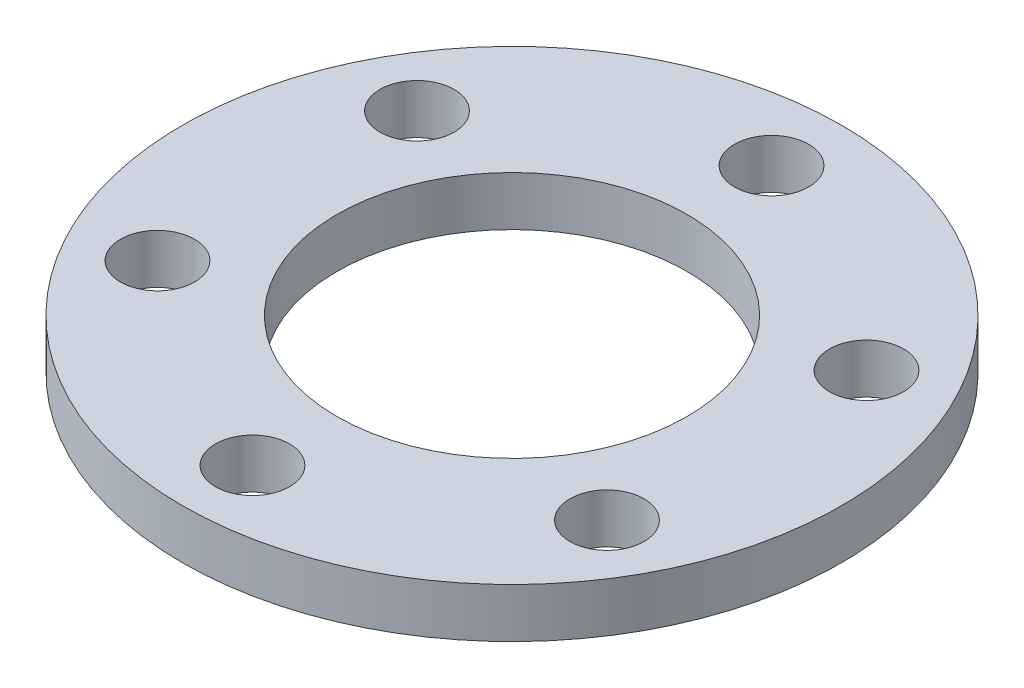
SolidWorks part; units mm, degrees
ref_plane "前视基准面" through (0, 0, 0) normal (0, 0, 1) x (1, 0, 0)
ref_plane "上视基准面" through (0, 0, 0) normal (0, 1, 0) x (1, 0, 0)
ref_plane "右视基准面" through (0, 0, 0) normal (1, 0, 0) x (0, 0, -1)
sketch "草图1" plane through (0, 0, 0) normal (0, 1, 0) x (1, 0, 0)
  circle A0 centre (0, 0) radius 40
  circle A1 centre (0, 0) radius 31.5 construction
  circle A2 centre (0, 0) radius 21.25
  circle A3 centre (0, 31.5) radius 4.5
  circle A4 centre (27.2798, 15.75) radius 4.5
  circle A5 centre (27.2798, -15.75) radius 4.5
  circle A6 centre (0, -31.5) radius 4.5
  circle A7 centre (-27.2798, -15.75) radius 4.5
  circle A8 centre (-27.2798, 15.75) radius 4.5
  dimension "D1" = 80
  dimension "D2" = 63
  dimension "D3" = 42.5
  dimension "D4" = 9
  dimension "D5" = 6
extrude "凸台-拉伸1" add sketch "草图1" along normal blind 6
